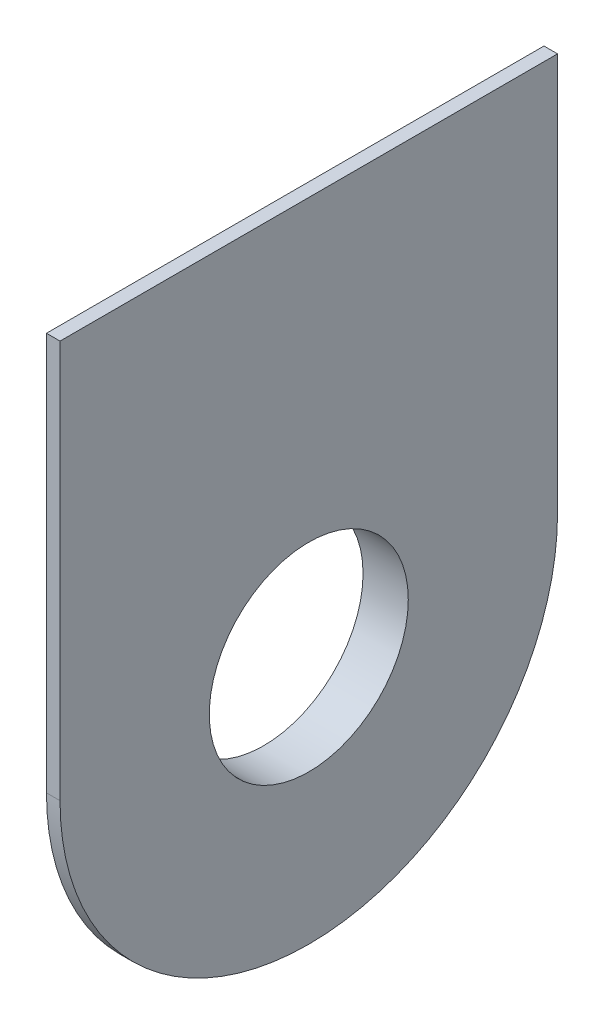
SolidWorks part; units mm, degrees
material "ABS"
ref_plane "Front Plane" through (0, 0, 0) normal (0, 0, 1) x (1, 0, 0)
ref_plane "Top Plane" through (0, 0, 0) normal (0, 1, 0) x (1, 0, 0)
ref_plane "Right Plane" through (0, 0, 0) normal (1, 0, 0) x (0, 0, -1)
sketch "Sketch1" plane through (74, 0, 0) normal (1, 0, 0) x (0, 0, -1)
  circle A0 centre (50, -18.3727) radius 25
  arc A1 (50, 46.3864) -> (50, -83.1319) centre (50, -18.3727) ccw construction
  circle A4 centre (50, -18.3727) radius 22
  circle A5 centre (50, -18.3727) radius 22
  dimension "D1" = 50
  dimension "D2" = 3
extrude "BEARING RING INSERT" add sketch "Sketch1" along normal blind 7 from offset 1
sketch "Sketch2" plane through (82, 0, 0) normal (1, 0, 0) x (0, 0, -1)
  line L0 (105, -18.3727) -> (105, 69.6273)
  line L1 (-5, -18.3727) -> (-5, 69.6273)
  line L2 (-5, 69.6273) -> (105, 69.6273)
  circle A0 centre (50, -18.3727) radius 22 construction
  circle A1 centre (50, -18.3727) radius 22
  arc A2 (-5, -18.3727) -> (105, -18.3727) centre (50, -18.3727) ccw
  dimension "D1" = 110
  dimension "D2" = 3
extrude "BULK EXTRUDE" add sketch "Sketch2" along normal blind 3
